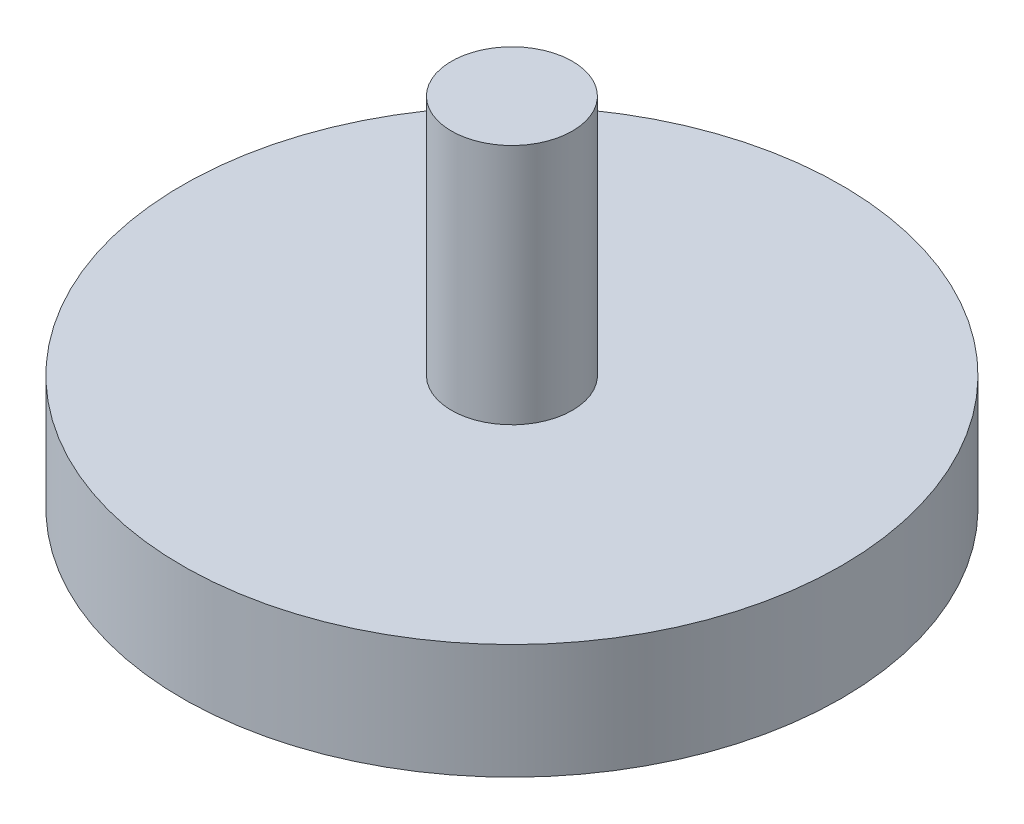
SolidWorks part; units mm, degrees
material "Acciaio al carbonio semplice"
ref_plane "Piano frontale" through (0, 0, 0) normal (0, 0, 1) x (1, 0, 0)
ref_plane "Piano superiore" through (0, 0, 0) normal (0, 1, 0) x (1, 0, 0)
ref_plane "Piano destro" through (0, 0, 0) normal (1, 0, 0) x (0, 0, -1)
sketch "Schizzo1" plane through (0, 0, 0) normal (0, 0, 1) x (1, 0, 0)
  line L1 (20, 68) -> (109, 68)
  line L2 (0, 0) -> (48, 0)
  line L3 (48, 0) -> (48, 5)
  line L4 (48, 5) -> (30, 5)
  line L5 (30, 5) -> (30, 30)
  line L6 (30, 30) -> (109, 30)
  line L7 (109, 30) -> (109, 68)
  line L8 (0, 0) -> (0, 148)
  line L9 (0, 148) -> (20, 148)
  line L10 (20, 148) -> (20, 68)
  line L11 (0, -1000) -> (0, 49000) construction
  point P1 (30, 17.5)
  dimension "D1" = 25
  dimension "D2" = 5
  dimension "D3" = 38
  dimension "D4" = 109
  dimension "D5" = 48
  dimension "D6" = 20
  dimension "D7" = 30
  dimension "D8" = 80
revolve "Rivoluzione1" add sketch "Schizzo1" angle 360 about L11
hole_wizard "Foro lamato per Bullone M5 a testa esagonale-1" positions "Schizzo2" profile "Schizzo3" counterbore size "M5" standard "ISO"
sketch "Schizzo2" plane through (0, 0, 0) normal (0, -1, 0) x (-1, 0, 0)
  point P0 (0, 38)
  point P2 (-38, 0)
  point P4 (0, -38)
  point P6 (38, 0)
  dimension "D1" = 38
  dimension "D2" = 38
  dimension "D3" = 38
  dimension "D4" = 38
sketch "Schizzo3" plane through (0, 0, -38) normal (1, 0, 0) x (0, 0, -1)
  line L0 (0, 0) -> (0, 49.6524)
  line L1 (0, 49.6524) -> (2.75, 48)
  line L2 (2.75, 48) -> (2.75, 3.5)
  line L3 (2.75, 3.5) -> (6.119, 3.5)
  line L4 (6.119, 3.5) -> (6.119, 0)
  line L5 (6.119, 0) -> (0, 0)
  line L10 (0, 49.6524) -> (-2.75, 48) construction
  line L11 (0, -6.35) -> (0, 107.95) construction
  dimension "Hole Dia." = 5.5
  dimension "Hole Depth" = 48
  dimension "C'Bore Dia." = 12.238
  dimension "C'Bore Depth" = 3.5
  dimension "Drill Angle" = 118
